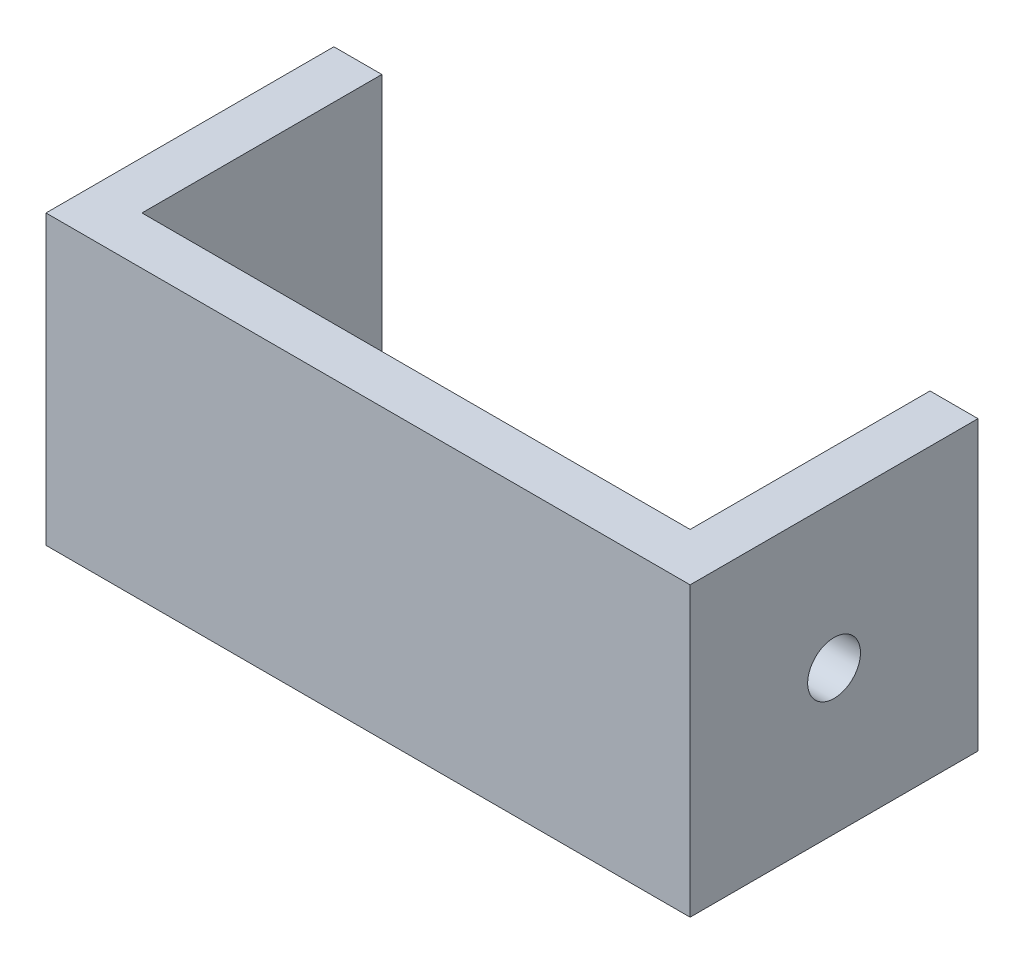
SolidWorks part; units mm, degrees
ref_plane "Front Plane" through (0, 0, 0) normal (0, 0, 1) x (1, 0, 0)
ref_plane "Top Plane" through (0, 0, 0) normal (0, 1, 0) x (1, 0, 0)
ref_plane "Right Plane" through (0, 0, 0) normal (1, 0, 0) x (0, 0, -1)
sketch "Sketch1" plane through (0, 0, 0) normal (0, 0, 1) x (1, 0, 0)
  line L1 (33.5625, 15) -> (-33.5625, 15)
  line L2 (33.5625, 15) -> (33.5625, -15)
  line L3 (33.5625, -15) -> (-33.5625, -15)
  line L4 (-33.5625, 15) -> (-33.5625, -15)
  line L5 (0, -15) -> (0, 15) construction
  line L6 (33.5625, 0) -> (-33.5625, 0) construction
  point P0 (0, 0)
  dimension "D1" = 30
  dimension "D2" = 67.125
extrude "Boss-Extrude1" add sketch "Sketch1" along normal blind 30
sketch "Sketch2" plane through (0, 0, 0) normal (0, 0, -1) x (-1, 0, 0)
  line L0 (-33.5625, 15) -> (33.5625, 15) construction
  line L1 (-28.5625, 15) -> (28.5625, 15)
  line L2 (-28.5625, 15) -> (-28.5625, -10)
  line L3 (-28.5625, -10) -> (28.5625, -10)
  line L4 (28.5625, 15) -> (28.5625, -10)
  line L5 (-33.5625, -15) -> (-33.5625, 15) construction
  line L6 (33.5625, 15) -> (33.5625, -15) construction
  line L7 (33.5625, -15) -> (-33.5625, -15) construction
  dimension "D1" = 5
  dimension "D2" = 5
  dimension "D3" = 5
extrude "Cut-Extrude1" cut sketch "Sketch2" against normal blind 25
sketch "Sketch3" plane through (33.5625, 0, 0) normal (1, 0, 0) x (0, 0, -1)
  line L0 (-30, 15) -> (0, 15) construction
  line L1 (-30, -15) -> (-30, 15) construction
  circle A0 centre (-15, 0) radius 2.75
  dimension "D1" = 5.5
  dimension "D2" = 15
  dimension "D3" = 15
extrude "Cut-Extrude2" cut sketch "Sketch3" against normal through all
